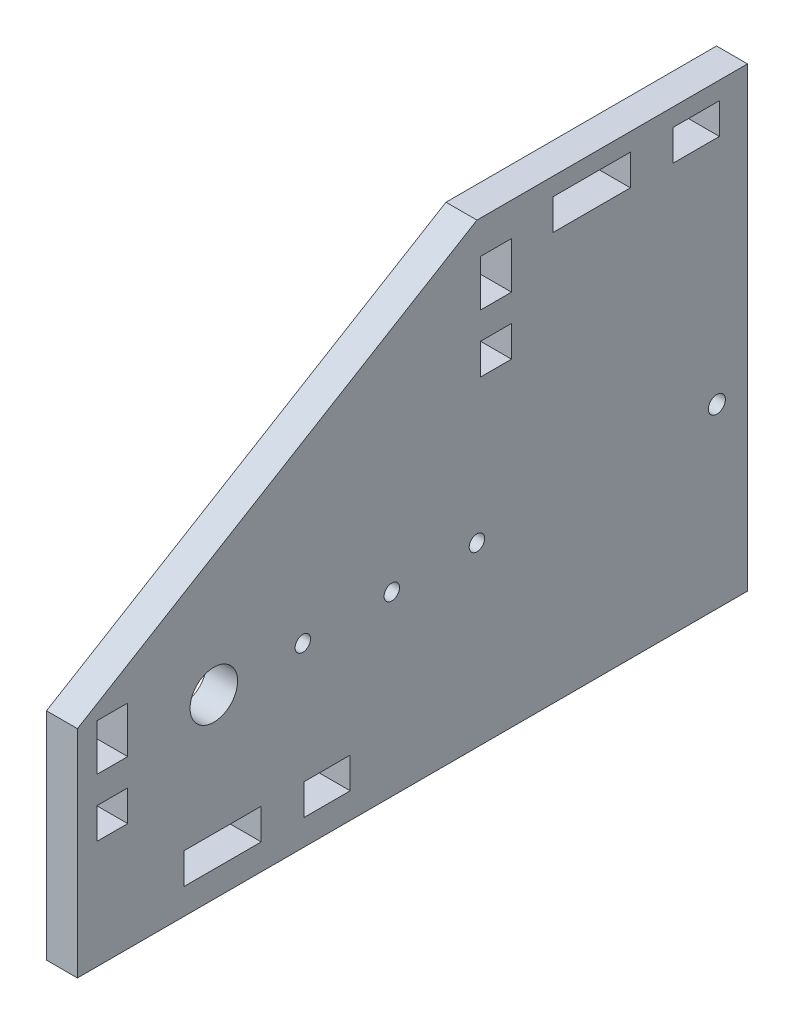
SolidWorks part; units mm, degrees
ref_plane "Front Plane" through (0, 0, 0) normal (0, 0, 1) x (1, 0, 0)
ref_plane "Top Plane" through (0, 0, 0) normal (0, 1, 0) x (1, 0, 0)
ref_plane "Right Plane" through (0, 0, 0) normal (1, 0, 0) x (0, 0, -1)
sketch "Sketch1" plane through (0, 0, 0) normal (1, 0, 0) x (0, 0, -1)
  line L0 (16.3304, 31.234) -> (26.3304, 31.234)
  line L1 (-45.1266, -21.4659) -> (41.4624, -21.4659)
  line L2 (-45.1266, -21.4659) -> (-45.1266, 6.4371)
  line L3 (6.4978, 37.5389) -> (41.4624, 37.5389)
  line L4 (41.4624, -21.4659) -> (41.4624, 37.5389)
  line L5 (-42.6266, 6.0625) -> (-38.6266, 6.0625)
  line L6 (-42.6266, 6.0625) -> (-42.6266, 0.0625)
  line L7 (-42.6266, 0.0625) -> (-38.6266, 0.0625)
  line L8 (-38.6266, 6.0625) -> (-38.6266, 0.0625)
  line L9 (-42.6266, -3.4375) -> (-38.6266, -3.4375)
  line L10 (-42.6266, -3.4375) -> (-42.6266, -7.4375)
  line L11 (-42.6266, -7.4375) -> (-38.6266, -7.4375)
  line L12 (-38.6266, -3.4375) -> (-38.6266, -7.4375)
  line L13 (-31.3747, -18.1111) -> (-21.3747, -18.1111)
  line L14 (-31.3747, -18.1111) -> (-31.3747, -14.1111)
  line L15 (-31.3747, -14.1111) -> (-21.3747, -14.1111)
  line L16 (-21.3747, -18.1111) -> (-21.3747, -14.1111)
  line L17 (-15.8748, -14.1425) -> (-9.8748, -14.1425)
  line L18 (-15.8748, -14.1425) -> (-15.8748, -18.1425)
  line L19 (-15.8748, -18.1425) -> (-9.8748, -18.1425)
  line L20 (-9.8748, -14.1425) -> (-9.8748, -18.1425)
  line L21 (16.3304, 31.234) -> (16.3304, 35.234)
  line L22 (16.3304, 35.234) -> (26.3304, 35.234)
  line L23 (26.3304, 31.234) -> (26.3304, 35.234)
  line L24 (31.8304, 35.234) -> (37.8304, 35.234)
  line L25 (31.8304, 35.234) -> (31.8304, 31.234)
  line L26 (31.8304, 31.234) -> (37.8304, 31.234)
  line L27 (37.8304, 35.234) -> (37.8304, 31.234)
  line L28 (6.9637, 33.2423) -> (10.9637, 33.2423)
  line L29 (6.9637, 33.2423) -> (6.9637, 27.2423)
  line L30 (6.9637, 27.2423) -> (10.9637, 27.2423)
  line L31 (10.9637, 33.2423) -> (10.9637, 27.2423)
  line L32 (6.9637, 23.7423) -> (10.9637, 23.7423)
  line L33 (6.9637, 23.7423) -> (6.9637, 19.7423)
  line L34 (6.9637, 19.7423) -> (10.9637, 19.7423)
  line L35 (10.9637, 23.7423) -> (10.9637, 19.7423)
  line L36 (-45.1266, 6.4371) -> (6.4978, 37.5389)
  line L37 (-38.6266, 0.0625) -> (-38.6266, -3.4375) construction
  line L38 (-21.3747, -14.1111) -> (-15.8748, -14.1425) construction
  line L39 (26.3304, 35.234) -> (31.8304, 35.234) construction
  line L40 (6.9637, 27.2423) -> (6.9637, 23.7423) construction
  line L41 (-42.6266, 6.0625) -> (-45.1266, 6.0625) construction
  circle A0 centre (-27.5022, 1.4243) radius 3.075
  circle A1 centre (-16.0022, 1.4243) radius 1
  circle A2 centre (-4.5022, 1.4243) radius 1
  circle A3 centre (6.4978, 1.4243) radius 1
  circle A4 centre (37.4978, 1.4243) radius 1.1
  circle A5 centre (-16.0022, 1.4243) radius 9.5 construction
  circle A6 centre (-27.5022, 1.4243) radius 2 construction
  circle A7 centre (-16.0022, 1.4243) radius 2.5 construction
  circle A8 centre (-4.5022, 1.4243) radius 9 construction
  circle A9 centre (-4.5022, 1.4243) radius 2.5 construction
  circle A10 centre (6.4978, 1.4243) radius 8.5 construction
  circle A11 centre (6.4978, 1.4243) radius 3 construction
  circle A12 centre (37.4978, 1.4243) radius 28 construction
  dimension "D1" = 11.5
  dimension "D2" = 11.5
  dimension "D3" = 11
  dimension "D4" = 31
extrude "Boss-Extrude1" add sketch "Sketch1" along normal blind 4
